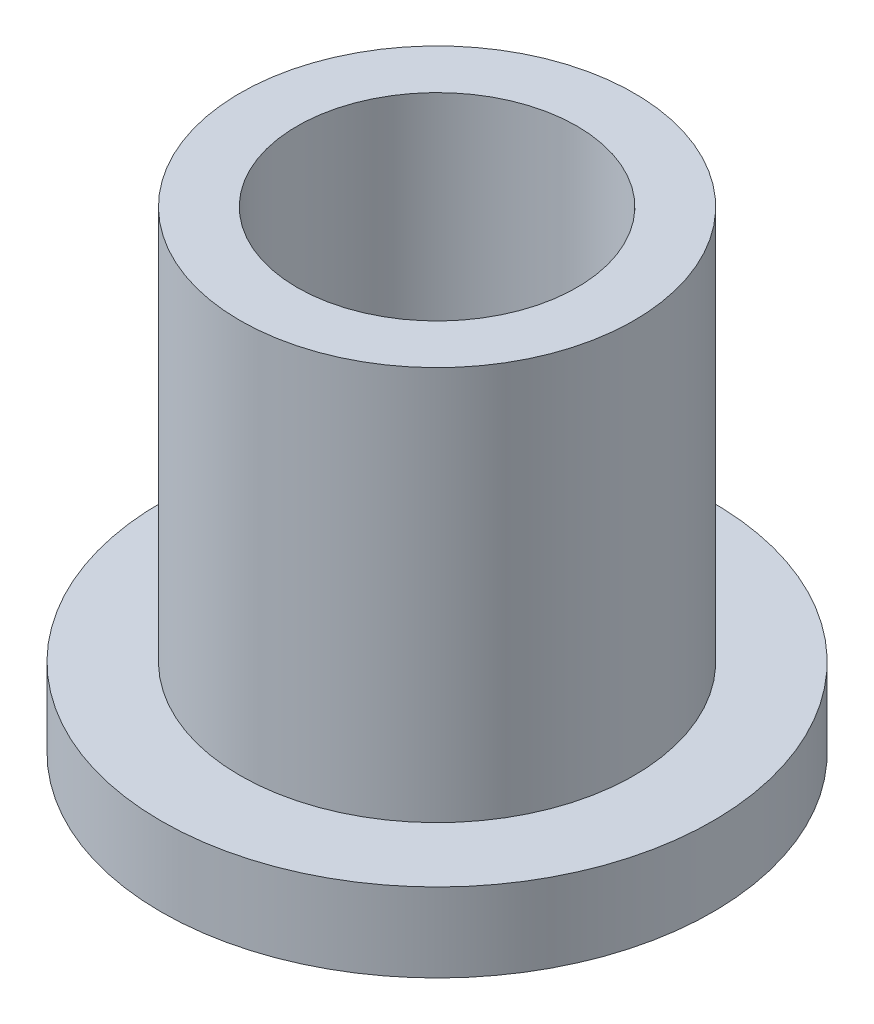
SolidWorks part; units mm, degrees
ref_plane "Front Plane" through (0, 0, 0) normal (0, 0, 1) x (1, 0, 0)
ref_plane "Top Plane" through (0, 0, 0) normal (0, 1, 0) x (1, 0, 0)
ref_plane "Right Plane" through (0, 0, 0) normal (1, 0, 0) x (0, 0, -1)
sketch "Sketch1" plane through (0, 0, 0) normal (0, 1, 0) x (1, 0, 0)
  circle A0 centre (0, 0) radius 7
  circle A2 centre (0, 0) radius 3.55
  dimension "D1" = 7.1
  dimension "D2" = 14
extrude "Boss-Extrude1" add sketch "Sketch1" along normal blind 2
sketch "Sketch2" plane through (0, 2, 0) normal (0, 1, 0) x (1, 0, 0)
  circle A0 centre (0, 0) radius 3.55
  circle A1 centre (0, 0) radius 5
  circle A2 centre (0, 0) radius 3.55 construction
  dimension "D1" = 10
extrude "Boss-Extrude2" add sketch "Sketch2" along normal blind 10
